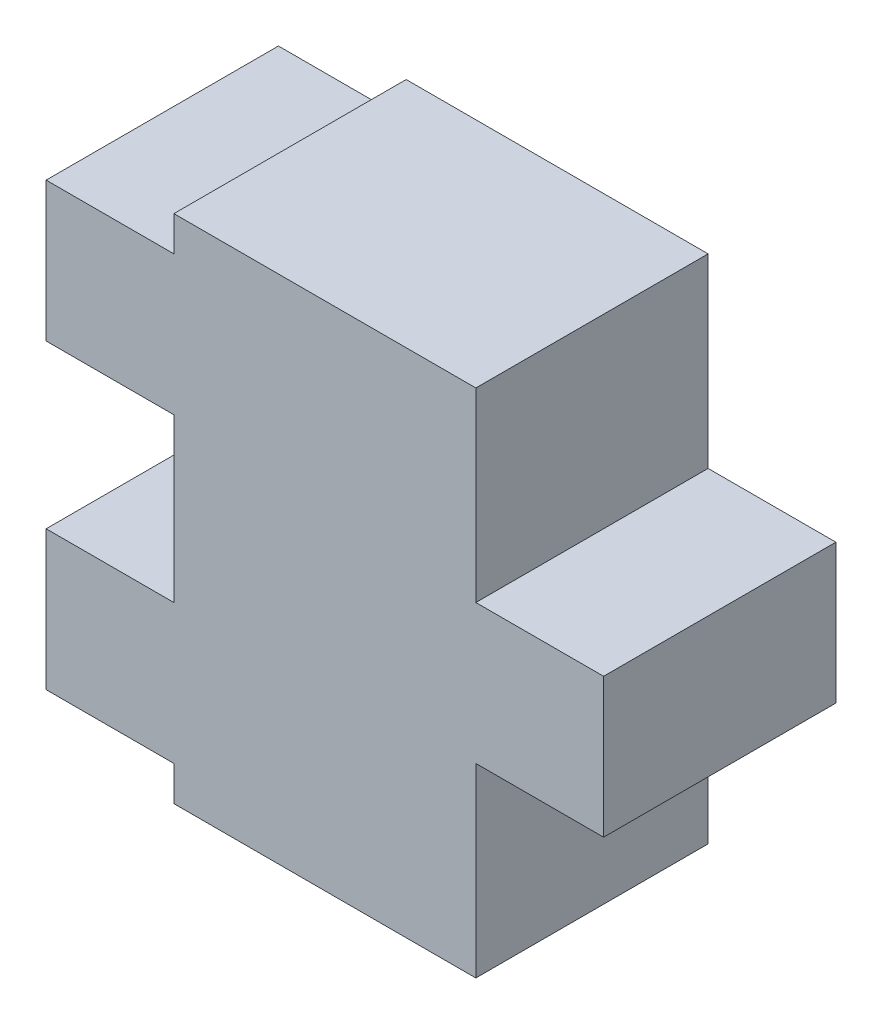
SolidWorks part; units mm, degrees
ref_plane "前视基准面" through (0, 0, 0) normal (0, 0, 1) x (1, 0, 0)
ref_plane "上视基准面" through (0, 0, 0) normal (0, 1, 0) x (1, 0, 0)
ref_plane "右视基准面" through (0, 0, 0) normal (1, 0, 0) x (0, 0, -1)
sketch "草图1" plane through (0, 0, 0) normal (0, 0, 1) x (1, 0, 0)
  line L0 (-0.65, 1.1) -> (-0.65, 0.95)
  line L1 (-0.65, 0.95) -> (-1.2, 0.95)
  line L2 (-1.2, 0.95) -> (-1.2, 0.35)
  line L3 (-1.2, 0.35) -> (-0.65, 0.35)
  line L4 (-0.65, 0.35) -> (-0.65, -0.35)
  line L5 (-0.65, -0.35) -> (-1.2, -0.35)
  line L6 (-1.2, -0.35) -> (-1.2, -0.95)
  line L7 (-1.2, -0.95) -> (-0.65, -0.95)
  line L8 (-0.65, -0.95) -> (-0.65, -1.1)
  line L9 (-0.65, -1.1) -> (0.65, -1.1)
  line L10 (0.65, -1.1) -> (0.65, -0.3)
  line L11 (0.65, -0.3) -> (1.2, -0.3)
  line L12 (1.2, -0.3) -> (1.2, 0.3)
  line L13 (1.2, 0.3) -> (0.65, 0.3)
  line L14 (0.65, 0.3) -> (0.65, 1.1)
  line L15 (0.65, 1.1) -> (-0.65, 1.1)
extrude "Component_Outline" add sketch "草图1" along normal blind 1 separate body
sketch3d "3D草图1"
  line L0 (0, 0, 0) -> (1, 0, 0)
  line L1 (0, 0, 0) -> (0, 1, 0)
  line L2 (0, 0, 0) -> (0, 0, 1)
  point P0 (0, 0, 0)
